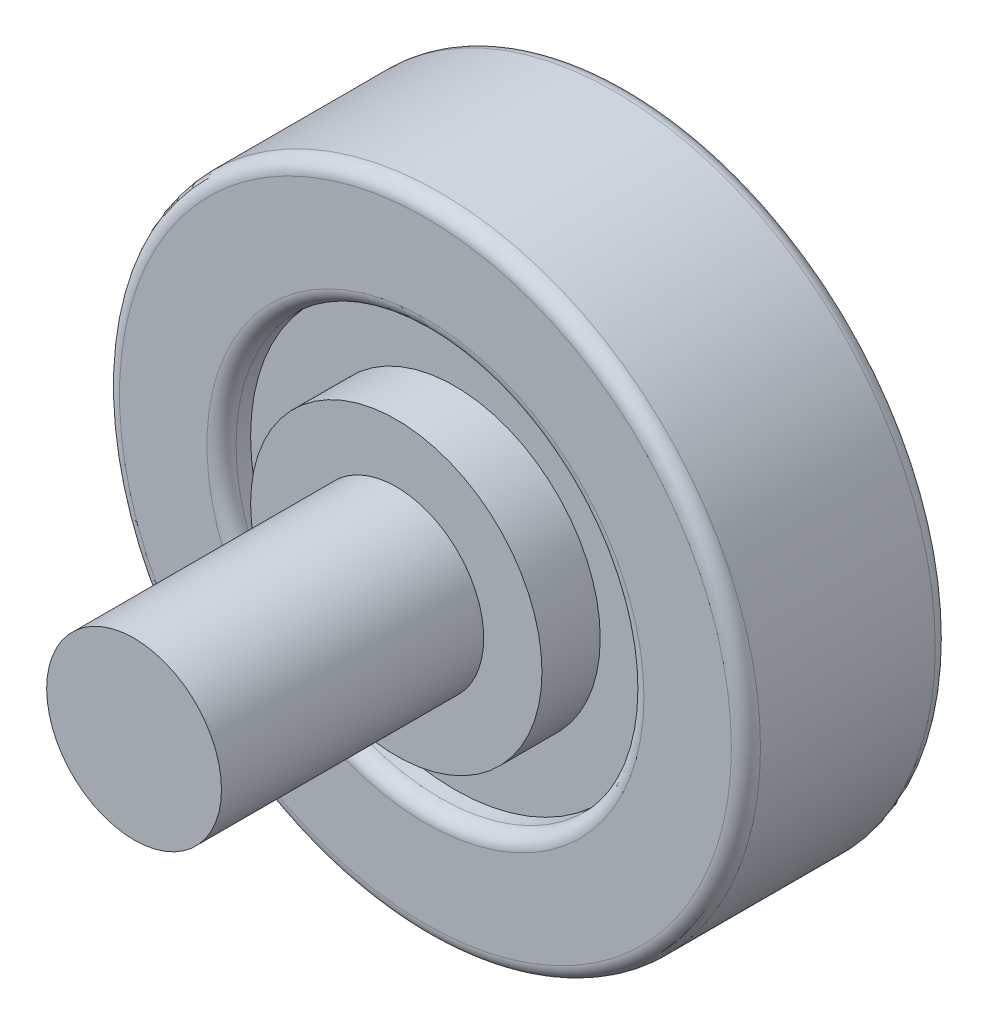
SolidWorks part; units mm, degrees
ref_plane "前视基准面" through (0, 0, 0) normal (0, 0, 1) x (1, 0, 0)
ref_plane "上视基准面" through (0, 0, 0) normal (0, 1, 0) x (1, 0, 0)
ref_plane "右视基准面" through (0, 0, 0) normal (1, 0, 0) x (0, 0, -1)
other "Configuration Table"
sketch "草图1" plane through (0, 0, 0) normal (0, 0, 1) x (1, 0, 0)
  circle A0 centre (0, 0) radius 11
  circle A1 centre (0, 0) radius 2.5
  dimension "D1" = 22
  dimension "D2" = 5
extrude "凸台-拉伸1" add sketch "草图1" along normal mid plane 7
sketch "草图2" plane through (0, 0, 3.5) normal (0, 0, 1) x (1, 0, 0)
  circle A0 centre (0, 0) radius 7
  dimension "D1" = 14
extrude "切除-拉伸1" cut sketch "草图2" against normal blind 1
mirror "镜向1" about plane through (0, 0, 0) normal (0, 0, 1) of "切除-拉伸1"
sketch "草图4" plane through (0, 0, -2.5) normal (0, 0, -1) x (-1, 0, 0)
  circle A0 centre (0, 0) radius 7
  dimension "D1" = 14
surface "曲面-拉伸1" sketch "草图4" parameters "D1"=14
split "分割1" trimming surface bodies 109 bodies to split 108 resulting bodies 110 111
fillet "圆角1" radius 0.5 4 edges at (7, 0, 3.5) (11, 0, 3.5) (11, 0, -3.5) (7, 0, -3.5)
sketch "草图5" plane through (0, 0, -2.5) normal (0, 0, -1) x (-1, 0, 0)
  circle A0 centre (0, 0) radius 3
  dimension "D1" = 6
extrude "凸台-拉伸3" add sketch "草图5" against normal offset from surface (16 mm away) 10 separate body up to face at (7.5, 0, 3.5) offset beyond the face yes
sketch "草图6" plane through (0, 0, 2.5) normal (0, 0, 1) x (1, 0, 0)
  circle A0 centre (0, 0) radius 5
  circle A1 centre (0, 0) radius 3 construction
  dimension "D1" = 2
extrude "凸台-拉伸4" add sketch "草图6" along normal blind 2 separate body
